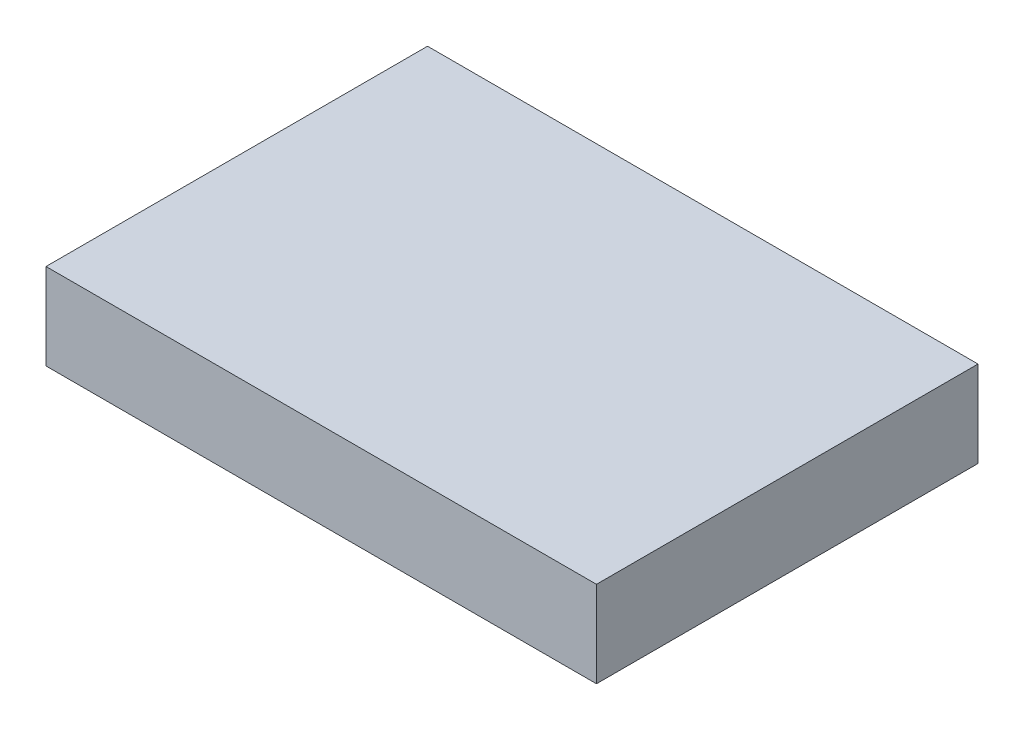
SolidWorks part; units mm, degrees
ref_plane "Front Plane" through (0, 0, 0) normal (0, 0, 1) x (1, 0, 0)
ref_plane "Top Plane" through (0, 0, 0) normal (0, 1, 0) x (1, 0, 0)
ref_plane "Right Plane" through (0, 0, 0) normal (1, 0, 0) x (0, 0, -1)
sketch "Sketch1" plane through (0, 0, 0) normal (0, 1, 0) x (1, 0, 0)
  line L1 (-12.3107, -20.13) -> (1.1051, -20.13)
  line L2 (-12.3107, -20.13) -> (-12.3107, -10.8312)
  line L3 (-12.3107, -10.8312) -> (1.1051, -10.8312)
  line L4 (1.1051, -20.13) -> (1.1051, -10.8312)
extrude "Boss-Extrude1" add sketch "Sketch1" along normal blind 2.1
